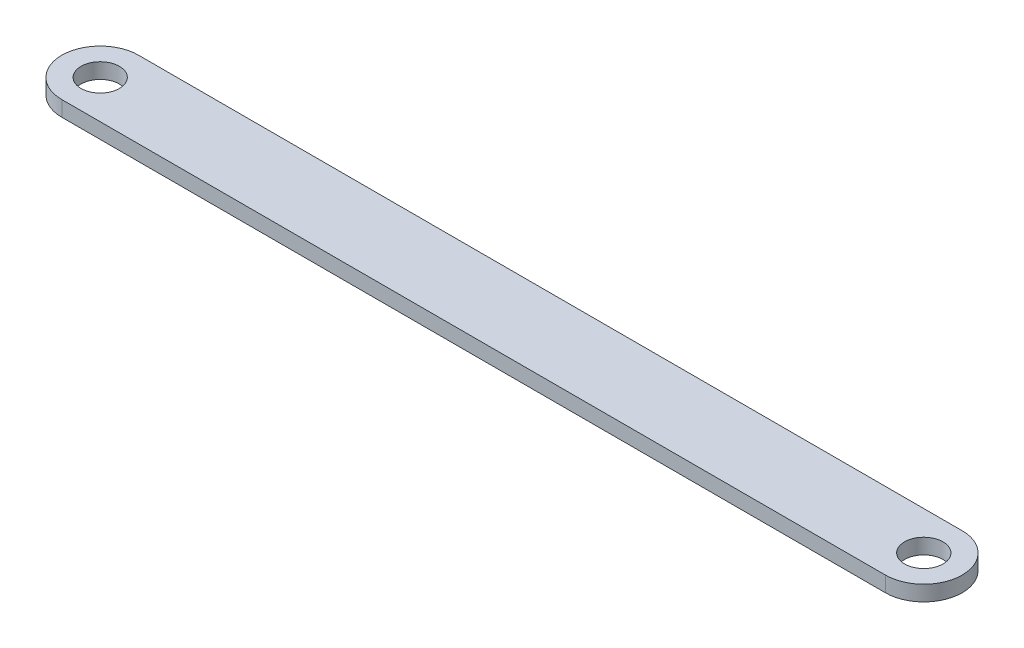
SolidWorks part; units mm, degrees
ref_plane "Front Plane" through (0, 0, 0) normal (0, 0, 1) x (1, 0, 0)
ref_plane "Top Plane" through (0, 0, 0) normal (0, 1, 0) x (1, 0, 0)
ref_plane "Right Plane" through (0, 0, 0) normal (1, 0, 0) x (0, 0, -1)
sketch "Sketch2" plane through (0, 0, 0) normal (0, 1, 0) x (1, 0, 0)
  line L0 (0, 0) -> (0, 12.7) construction
  line L1 (0, 0) -> (0, -12.7) construction
  line L2 (0, 0) -> (12.7, 0) construction
  line L3 (0, 0) -> (-272.4, 0) construction
  line L4 (-272.4, 0) -> (-272.4, 12.7) construction
  line L5 (-272.4, 0) -> (-272.4, -12.7) construction
  line L6 (-272.4, 0) -> (-285.1, 0) construction
  line L7 (-272.4, -12.7) -> (0, -12.7)
  line L8 (-272.4, 12.7) -> (0, 12.7)
  circle A0 centre (0, 0) radius 6.35
  arc A1 (0, 12.7) -> (0, -12.7) centre (0, 0) cw
  circle A2 centre (-272.4, 0) radius 6.35
  arc A3 (-272.4, 12.7) -> (-272.4, -12.7) centre (-272.4, 0) ccw
  point P13 (-285.1, 0)
  dimension "D1" = 12.7
  dimension "D6" = 12.7
  dimension "D2" = 12.7
  dimension "D3" = 12.7
  dimension "D4" = 12.7
  dimension "D5" = 272.4
  dimension "D7" = 12.7
  dimension "D8" = 12.7
  dimension "D9" = 12.7
extrude "Boss-Extrude1" add sketch "Sketch2" along normal blind 5.08
